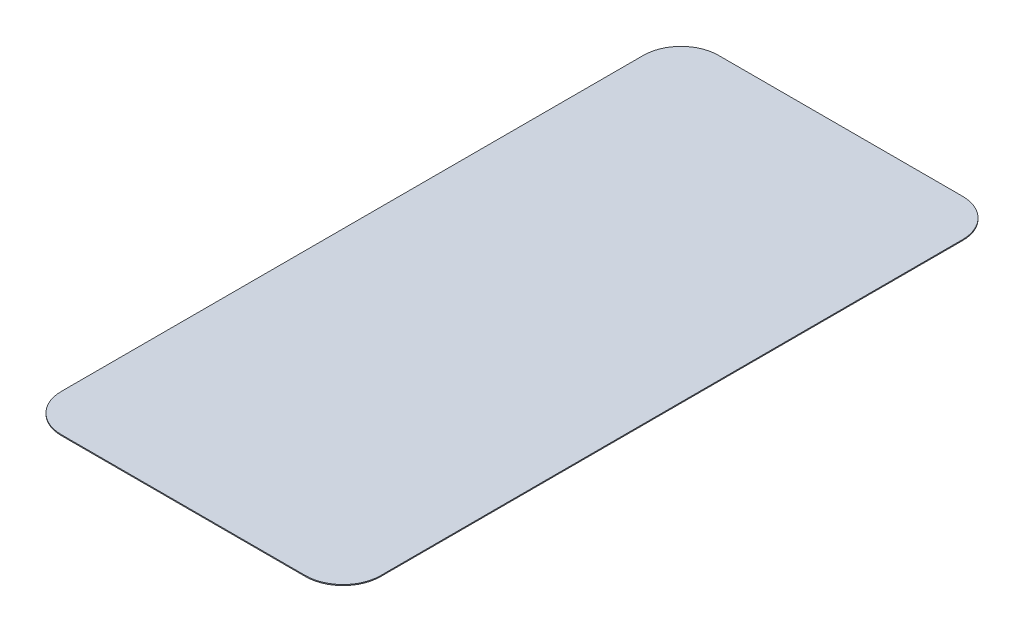
SolidWorks part; units mm, degrees
ref_plane "Front Plane" through (0, 0, 0) normal (0, 0, 1) x (1, 0, 0)
ref_plane "Top Plane" through (0, 0, 0) normal (0, 1, 0) x (1, 0, 0)
ref_plane "Right Plane" through (0, 0, 0) normal (1, 0, 0) x (0, 0, -1)
sketch "Sketch1" plane through (0, 0, 0) normal (0, 1, 0) x (1, 0, 0)
  line L1 (-65, 175) -> (65, 175)
  line L2 (-85, 155) -> (-85, -155)
  line L3 (-65, -175) -> (65, -175)
  line L4 (85, 155) -> (85, -155)
  line L5 (-85, 175) -> (85, -175) construction
  line L6 (-85, -175) -> (85, 175) construction
  arc A0 (85, -155) -> (65, -175) centre (65, -155) cw
  arc A1 (-65, -175) -> (-85, -155) centre (-65, -155) cw
  arc A2 (85, 155) -> (65, 175) centre (65, 155) ccw
  arc A3 (-85, 155) -> (-65, 175) centre (-65, 155) cw
  point P0 (0, 0)
  dimension "D1" = 20
extrude "Boss-Extrude1" add sketch "Sketch1" along normal blind 0.5
